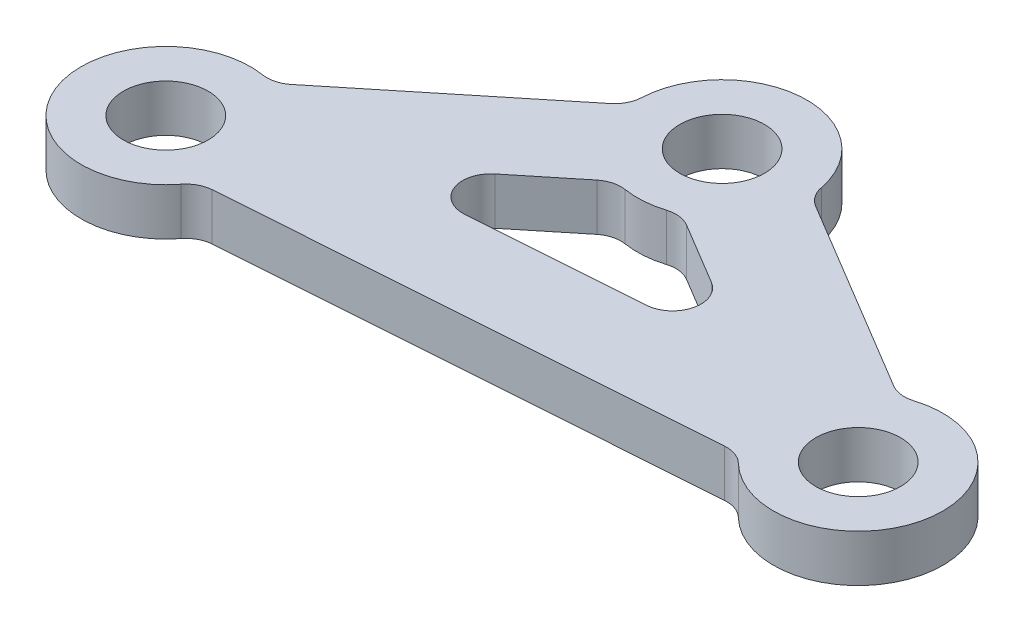
SolidWorks part; units mm, degrees
ref_plane "前视基准面" through (0, 0, 0) normal (0, 0, 1) x (1, 0, 0)
ref_plane "上视基准面" through (0, 0, 0) normal (0, 1, 0) x (1, 0, 0)
ref_plane "右视基准面" through (0, 0, 0) normal (1, 0, 0) x (0, 0, -1)
sketch "草图1" plane through (0, 0, 0) normal (0, 1, 0) x (1, 0, 0)
  line L3 (-24.5298, -13.4149) -> (26.2613, -9.7903)
  line L4 (9.0374, 17.1077) -> (29.7227, 4.7189)
  line L5 (-11.3001, 15.6563) -> (-30.0165, 0.4557)
  line L6 (-8.8548, -2.2709) -> (9.1626, -0.9851)
  line L7 (3.8993, 8.5286) -> (10.4905, 4.581)
  line L8 (-4.9958, 7.8939) -> (-10.9597, 3.0503)
  arc A0 (-32.3827, -0.1777) -> (-26.689, -14.5715) centre (-33.8073, -9.0643) ccw
  arc A1 (-2.6296, 8.5273) -> (1.4671, 8.8197) centre (-1.205, 17.4138) ccw
  arc A2 (28.5628, -10.6285) -> (32.1548, 4.4279) centre (34.8269, -4.1663) ccw
  circle A4 centre (34.8269, -4.1663) radius 4.5
  circle A5 centre (-1.205, 17.4138) radius 4.5
  arc A6 (-8.8548, -2.2709) -> (-10.9597, 3.0503) centre (-9.0684, 0.7215) cw
  arc A7 (9.1626, -0.9851) -> (10.4905, 4.581) centre (8.9491, 2.0073) ccw
  circle A8 centre (-33.8073, -9.0643) radius 4.5
  arc A9 (7.6329, 19.1145) -> (-10.1948, 17.8422) centre (-1.205, 17.4138) ccw
  arc A10 (-30.0165, 0.4557) -> (-32.3827, -0.1777) centre (-31.9078, 2.7844) cw
  arc A11 (-11.3001, 15.6563) -> (-10.1948, 17.8422) centre (-13.1914, 17.985) ccw
  arc A12 (-24.5298, -13.4149) -> (-26.689, -14.5715) centre (-24.3163, -16.4073) ccw
  arc A13 (26.2613, -9.7903) -> (28.5628, -10.6285) centre (26.4748, -12.7826) cw
  arc A14 (29.7227, 4.7189) -> (32.1548, 4.4279) centre (31.2641, 7.2926) ccw
  arc A15 (9.0374, 17.1077) -> (7.6329, 19.1145) centre (10.5788, 19.6814) cw
  arc A16 (-4.9958, 7.8939) -> (-2.6296, 8.5273) centre (-3.1045, 5.5651) cw
  arc A17 (3.8993, 8.5286) -> (1.4671, 8.8197) centre (2.3578, 5.9549) ccw
  point P3 (-49.2691, -15.1804)
  point P4 (51.0006, -8.0248)
  point P5 (-1.6395, 23.5022)
  dimension "D6" = 3
  dimension "D7" = 3
  dimension "D8" = 3
  dimension "D3" = 3
  dimension "D4" = 3
  dimension "D5" = 3
  dimension "D9" = 3
  dimension "D10" = 3
  dimension "D11" = 3
  dimension "D12" = 3
  dimension "D1" = 42
  dimension "D2" = 42
extrude "凸台-拉伸1" add sketch "草图1" along normal blind 5
